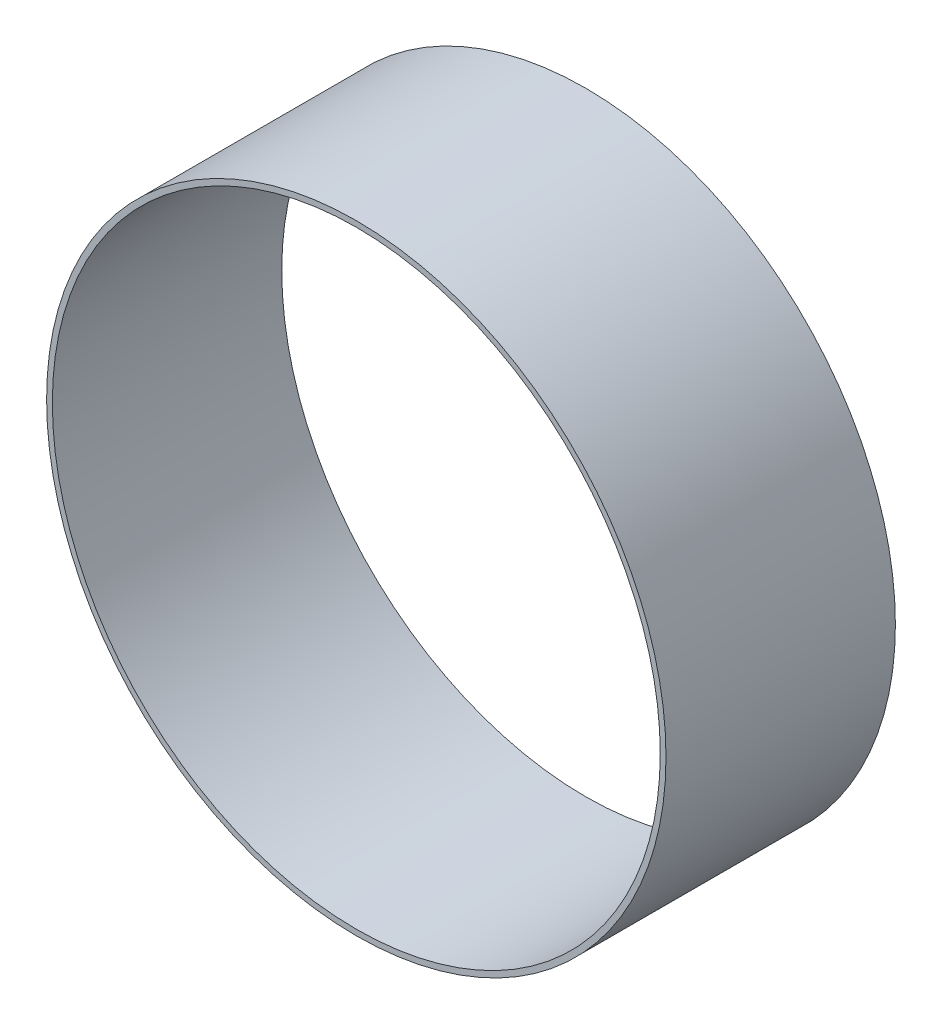
SolidWorks part; units mm, degrees
ref_plane "前视基准面" through (0, 0, 0) normal (0, 0, 1) x (1, 0, 0)
ref_plane "上视基准面" through (0, 0, 0) normal (0, 1, 0) x (1, 0, 0)
ref_plane "右视基准面" through (0, 0, 0) normal (1, 0, 0) x (0, 0, -1)
sketch "草图1" plane through (0, 0, 0) normal (0, 0, 1) x (1, 0, 0)
  circle A0 centre (0, 0) radius 10.6
  circle A1 centre (0, 0) radius 10.8
extrude "凸台-拉伸1" add sketch "草图1" along normal blind 8
